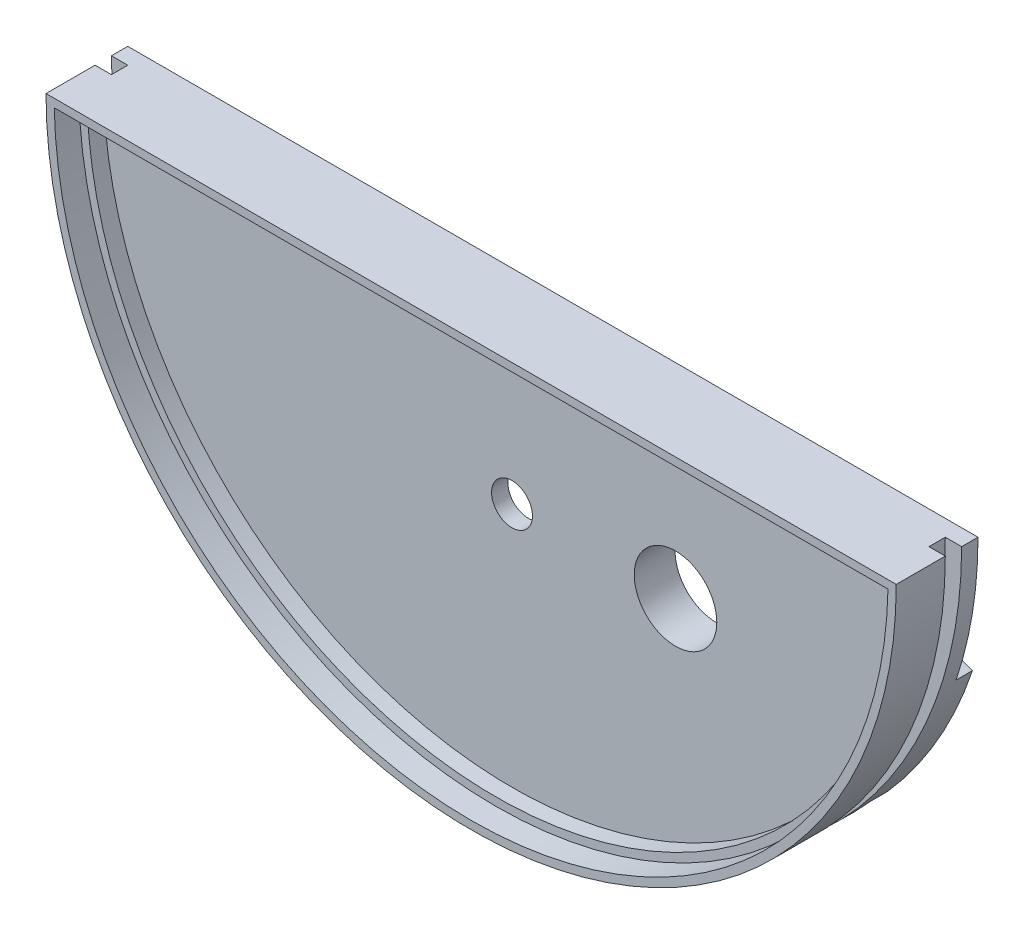
SolidWorks part; units mm, degrees
material "Acrylic (Medium-high impact)"
ref_plane "Front Plane" through (0, 0, 0) normal (0, 0, 1) x (1, 0, 0)
ref_plane "Top Plane" through (0, 0, 0) normal (0, 1, 0) x (1, 0, 0)
ref_plane "Right Plane" through (0, 0, 0) normal (1, 0, 0) x (0, 0, -1)
sketch "Sketch1" plane through (0, 0, 0) normal (0, 0, 1) x (1, 0, 0)
  line L0 (-52, 0) -> (52, 0)
  arc A0 (-52, 0) -> (52, 0) centre (0, 0) ccw
  circle A1 centre (20, -20) radius 5.05
  dimension "D2" = 10.1
  dimension "D1" = 104
  dimension "D3" = 20
  dimension "D4" = 20
extrude "Boss-Extrude1" add sketch "Sketch1" against normal blind 5
sketch "Sketch2" plane through (0, 0, 0) normal (0, 0, 1) x (1, 0, 0)
  line L0 (49.96, -2) -> (-49.96, -2)
  line L1 (52, 0) -> (-52, 0)
  line L2 (52, 0) -> (-52, 0)
  arc A0 (-49.96, -2) -> (49.96, -2) centre (0, 0) ccw
  arc A1 (-52, 0) -> (52, 0) centre (0, 0) ccw
  arc A2 (-52, 0) -> (52, 0) centre (0, 0) ccw
  dimension "D1" = 0
  dimension "D2" = 2
extrude "Boss-Extrude2" add sketch "Sketch2" along normal blind 5
ref_plane "Plane1" through (0, 0, 4) normal (0, 0, 1) x (1, 0, 0)
ref_plane "Plane2" through (0, -52, 0) normal (0, -1, 0) x (-1, 0, 0)
sketch "Sketch5" plane through (0, 0, -5) normal (0, 0, -1) x (-1, 0, 0)
  line L0 (10, -48.9898) -> (10.4, -50.9494)
  line L1 (52, 0) -> (-52, 0)
  line L2 (52, 0) -> (-52, 0)
  line L3 (-10, -48.9898) -> (-10.4, -50.9494)
  line L4 (-37.4264, -33.1552) -> (-38.9235, -34.4814)
  line L5 (-47.4264, -15.8346) -> (-49.3235, -16.468)
  line L12 (47.4264, -15.8346) -> (49.3235, -16.468)
  line L13 (37.4264, -33.1552) -> (38.9235, -34.4814)
  line L14 (-47.4264, 15.8346) -> (-49.3235, 16.468) [skipped]
  line L15 (-37.4264, 33.1552) -> (-38.9235, 34.4814) [skipped]
  line L16 (-10, 48.9898) -> (-10.4, 50.9494) [skipped]
  line L17 (10, 48.9898) -> (10.4, 50.9494) [skipped]
  line L18 (37.4264, 33.1552) -> (38.9235, 34.4814) [skipped]
  line L19 (47.4264, 15.8346) -> (49.3235, 16.468) [skipped]
  arc A0 (-10, -48.9898) -> (10, -48.9898) centre (0, 0) ccw
  arc A1 (-52, 0) -> (52, 0) centre (0, 0) ccw
  arc A2 (-52, 0) -> (52, 0) centre (0, 0) ccw
  arc A3 (-47.4264, -15.8346) -> (-37.4264, -33.1552) centre (0, 0) ccw
  arc A7 (37.4264, -33.1552) -> (47.4264, -15.8346) centre (0, 0) ccw
  arc A8 (-37.4264, 33.1552) -> (-47.4264, 15.8346) centre (0, 0) ccw [skipped]
  arc A9 (10, 48.9898) -> (-10, 48.9898) centre (0, 0) ccw [skipped]
  arc A10 (47.4264, 15.8346) -> (37.4264, 33.1552) centre (0, 0) ccw [skipped]
  point P30 (0, 0)
  arc M22 (-52, 0) -> (52, 0) centre (0, 0) ccw
  dimension "D2" = 50
  dimension "D3" = 10
  dimension "D4" = 10
  dimension "D1" = 0
  dimension "D5" = 6
extrude "Boss-Extrude4" add sketch "Sketch5" along normal blind 2 contours A3 L5 L4 M22 | A0 L3 L0 M22 | A7 L13 L12 M22
sketch "Sketch6" plane through (0, 0, -5) normal (0, 0, -1) x (-1, 0, 0)
  line L0 (-52, 0) -> (52, 0) construction
  circle A0 centre (0, -20) radius 9.5
  circle A2 centre (-20, -20) radius 5.05 construction
  circle A3 centre (-20, -20) radius 5.05
  dimension "D1" = 19
  dimension "D2" = 20
extrude "Cut-Extrude1" cut sketch "Sketch6" against normal blind 3
sketch "Sketch7" plane through (0, 0, -2) normal (0, 0, -1) x (-1, 0, 0)
  circle A0 centre (0, -20) radius 2.5
  dimension "D1" = 5
extrude "Cut-Extrude2" cut sketch "Sketch7" against normal through all
sketch "Sketch8" plane through (0, 0, -5) normal (0, 0, -1) x (-1, 0, 0)
  circle A0 centre (20, -20) radius 5
  circle A1 centre (-20, -20) radius 5.05 construction
  circle A2 centre (-20, -20) radius 5.05
  dimension "D2" = 10
  dimension "D1" = 20
extrude "Boss-Extrude5" add sketch "Sketch8" along normal blind 3 contours A0
sketch "Sketch9" plane through (0, 0, 5) normal (0, 0, 1) x (1, 0, 0)
  line L1 (52, 0) -> (-52, 0) construction
  line L4 (52, 0) -> (-52, 0)
  line L5 (50.9902, -1) -> (-50.9902, -1)
  arc A0 (-52, 0) -> (52, 0) centre (0, 0) ccw construction
  arc A1 (-52, 0) -> (52, 0) centre (0, 0) ccw
  arc A2 (-50.9902, -1) -> (50.9902, -1) centre (0, 0) ccw
  line M4 (-49.96, -2) -> (49.96, -2)
  arc M5 (49.96, -2) -> (-49.96, -2) centre (0, 0) cw
  dimension "D2" = 1
extrude "Cut-Extrude3" cut sketch "Sketch9" against normal blind 3 contours M4 M5 | L5 A2 M5 M4
sketch "Sketch10" plane through (0, 0, 0) normal (0, 1, 0) x (1, 0, 0)
  line L0 (52, 5) -> (-52, 5) construction
  line L1 (58.5963, 1) -> (50, 1)
  line L2 (58.5963, 1) -> (58.5963, 3)
  line L3 (58.5963, 3) -> (50, 3)
  line L4 (50, 1) -> (50, 3)
  line L5 (52, 5) -> (52, -5) construction
  dimension "D1" = 2
  dimension "D2" = 2
  dimension "D3" = 2
ref_axis "Axis1" through (0, 0, -7) along (0, 0, 1)
revolve "Cut-Revolve1" cut sketch "Sketch10" angle 180 about axis through (0, 0, -7) along (0, 0, 1)
